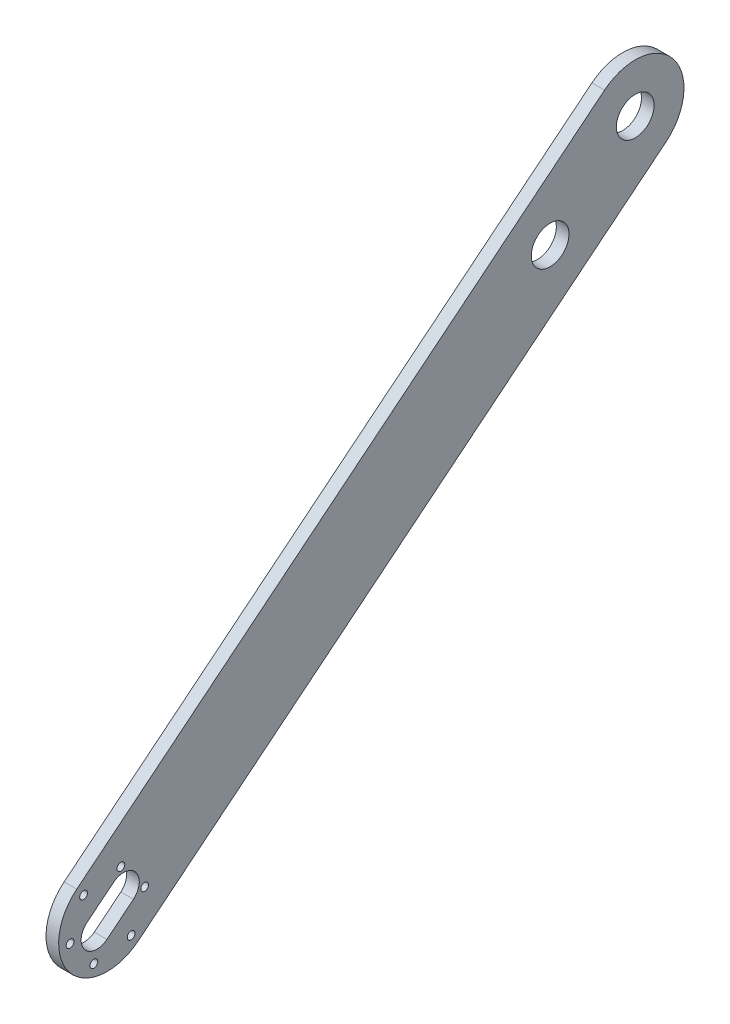
SolidWorks part; units mm, degrees
ref_plane "Front Plane" through (0, 0, 0) normal (0, 0, 1) x (1, 0, 0)
ref_plane "Top Plane" through (0, 0, 0) normal (0, 1, 0) x (1, 0, 0)
ref_plane "Right Plane" through (0, 0, 0) normal (1, 0, 0) x (0, 0, -1)
sketch "Sketch1" plane through (0, 0, 0) normal (1, 0, 0) x (0, 0, -1)
  line L0 (-105.1172, 0) -> (115.6845, 0) construction
  line L1 (0, 102.7534) -> (0, -99.1383) construction
  line L2 (-136.0213, -110.3214) -> (80.6672, 65.4259) construction
  line L3 (-148.6196, -94.7882) -> (68.0688, 80.9591)
  line L4 (-123.4229, -125.8546) -> (93.2655, 49.8927)
  line L5 (-129.4197, -104.9671) -> (-140.2929, -113.786) construction
  line L6 (-125.3252, -110.0154) -> (-136.1984, -118.8343)
  line L7 (-133.5141, -99.9188) -> (-144.3874, -108.7377)
  line L8 (-132.3489, -71.9866) -> (-94.8331, -118.2419) construction
  line L9 (-154.7728, -135.5086) -> (-96.9334, -88.5974) construction
  arc A0 (-148.6196, -94.7882) -> (-123.4229, -125.8546) centre (-136.0213, -110.3214) ccw
  arc A1 (93.2655, 49.8927) -> (68.0688, 80.9591) centre (80.6672, 65.4259) ccw
  circle A2 centre (80.6672, 65.4259) radius 7.7375
  circle A4 centre (-136.0213, -110.3214) radius 15.5 construction
  circle A5 centre (45.7174, 37.0796) radius 7.7375
  arc A6 (-125.3252, -110.0154) -> (-133.5141, -99.9188) centre (-129.4197, -104.9671) ccw
  arc A7 (-144.3874, -108.7377) -> (-136.1984, -118.8343) centre (-140.2929, -113.786) ccw
  circle A8 centre (-141.5648, -124.7962) radius 1.6
  circle A9 centre (-151.3286, -112.7579) radius 1.6
  circle A10 centre (-145.785, -98.2832) radius 1.6
  circle A11 centre (-130.4777, -95.8466) radius 1.6
  circle A12 centre (-120.714, -107.8849) radius 1.6
  circle A13 centre (-126.2575, -122.3596) radius 1.6
  point P7 (-27.6771, -22.4477)
  point P20 (-134.8563, -109.3765)
  point P27 (-151.5545, -122.9198)
  dimension "D3" = 31
  dimension "D4" = 15.475
  dimension "D5" = 15.475
  dimension "D6" = 45
  dimension "D7" = 47
  dimension "D11" = 3.2
  dimension "D1" = 279
  dimension "D2" = 40
  dimension "D8" = 18.5
  dimension "D9" = 14
  dimension "D10" = 13
  dimension "D12" = 6
extrude "Boss-Extrude1" add sketch "Sketch1" along normal blind 5.1784
